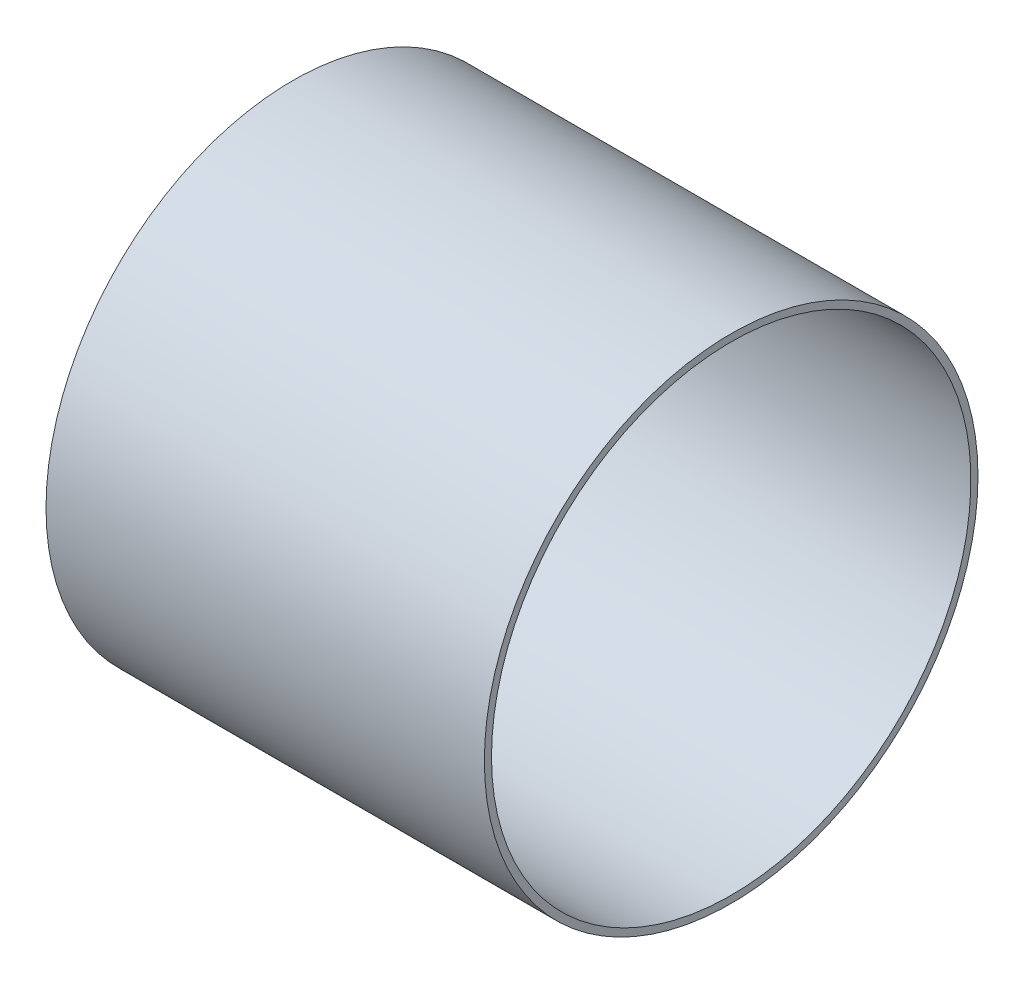
SolidWorks part; units mm, degrees
ref_plane "Front Plane" through (0, 0, 0) normal (0, 0, 1) x (1, 0, 0)
ref_plane "Top Plane" through (0, 0, 0) normal (0, 1, 0) x (1, 0, 0)
ref_plane "Right Plane" through (0, 0, 0) normal (1, 0, 0) x (0, 0, -1)
sketch "Sketch1" plane through (0, 0, 0) normal (1, 0, 0) x (0, 0, -1)
  circle A0 centre (0, 0) radius 57.15
  circle A1 centre (0, 0) radius 55.499
  dimension "D1" = 1.651
  dimension "D2" = 114.3
extrude "Boss-Extrude1" add sketch "Sketch1" along normal blind 101.5009
